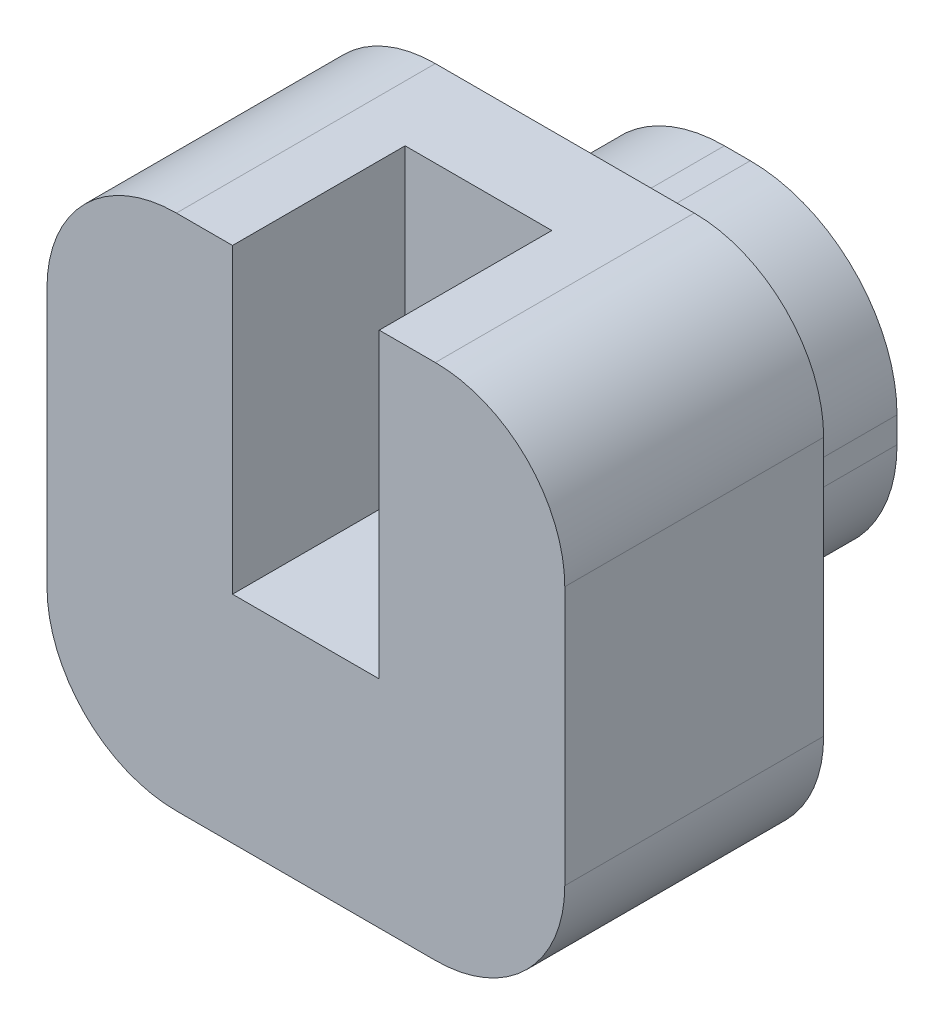
SolidWorks part; units mm, degrees
ref_plane "Спереди" through (0, 0, 0) normal (0, 0, 1) x (1, 0, 0)
ref_plane "Сверху" through (0, 0, 0) normal (0, 1, 0) x (1, 0, 0)
ref_plane "Справа" through (0, 0, 0) normal (1, 0, 0) x (0, 0, -1)
sketch "Эскиз1" plane through (0, 0, 0) normal (0, 0, 1) x (1, 0, 0)
  line L1 (-0.15, -1.85) -> (0.15, -1.85)
  line L2 (-1.85, -0.15) -> (-1.85, 0.15)
  line L3 (-0.15, 1.85) -> (0.15, 1.85)
  line L4 (1.85, -0.15) -> (1.85, 0.15)
  line L5 (-1.85, -1.85) -> (1.85, 1.85) construction
  line L6 (-1.85, 1.85) -> (1.85, -1.85) construction
  arc A0 (-1.85, -0.15) -> (-0.15, -1.85) centre (-0.15, -0.15) ccw
  arc A1 (1.85, 0.15) -> (0.15, 1.85) centre (0.15, 0.15) ccw
  arc A2 (-0.15, 1.85) -> (-1.85, 0.15) centre (-0.15, 0.15) ccw
  arc A3 (1.85, -0.15) -> (0.15, -1.85) centre (0.15, -0.15) cw
  point P0 (0, 0)
  dimension "D3" = 1.7
  dimension "D1" = 3.7
  dimension "D2" = 3.7
extrude "Бобышка-Вытянуть1" add sketch "Эскиз1" along normal blind 2
sketch "Эскиз2" plane through (0, 0, 2) normal (0, 0, 1) x (1, 0, 0)
  line L1 (-1.5, -3) -> (1.5, -3)
  line L2 (-3, -1.5) -> (-3, 1.5)
  line L3 (-1.5, 3) -> (1.5, 3)
  line L4 (3, -1.5) -> (3, 1.5)
  line L5 (-3, -3) -> (3, 3) construction
  line L6 (-3, 3) -> (3, -3) construction
  arc A0 (1.5, -3) -> (3, -1.5) centre (1.5, -1.5) ccw
  arc A1 (-1.5, -3) -> (-3, -1.5) centre (-1.5, -1.5) cw
  arc A2 (3, 1.5) -> (1.5, 3) centre (1.5, 1.5) ccw
  arc A3 (-3, 1.5) -> (-1.5, 3) centre (-1.5, 1.5) cw
  point P0 (0, 0)
  dimension "D3" = 1.5
  dimension "D1" = 6
  dimension "D2" = 6
extrude "Бобышка-Вытянуть2" add sketch "Эскиз2" along normal blind 3 contours A3 L2 A1 L1 A0 L4 A2 L3
sketch "Эскиз4" plane through (0, 3, 0) normal (0, 1, 0) x (1, 0, 0)
  line L0 (3, -5) -> (3, -2) construction
  line L1 (-1.5, -5) -> (1.5, -5) construction
  line L2 (-0.85, -5) -> (0.85, -5)
  line L3 (-0.85, -5) -> (-0.85, -3)
  line L4 (-0.85, -3) -> (0.85, -3)
  line L5 (0.85, -5) -> (0.85, -3)
  line L6 (-0.85, -5) -> (0.85, -3) construction
  line L7 (-0.85, -3) -> (0.85, -5) construction
  point P3 (0, -4)
  point P8 (0, -5)
  dimension "D1" = 2
  dimension "D2" = 1.7
  dimension "D3" = 3
extrude "Вырез-Вытянуть1" cut sketch "Эскиз4" against normal blind 3.5
equation "\"D3@Эскиз4\"=\"D1@Эскиз2\"/2"
